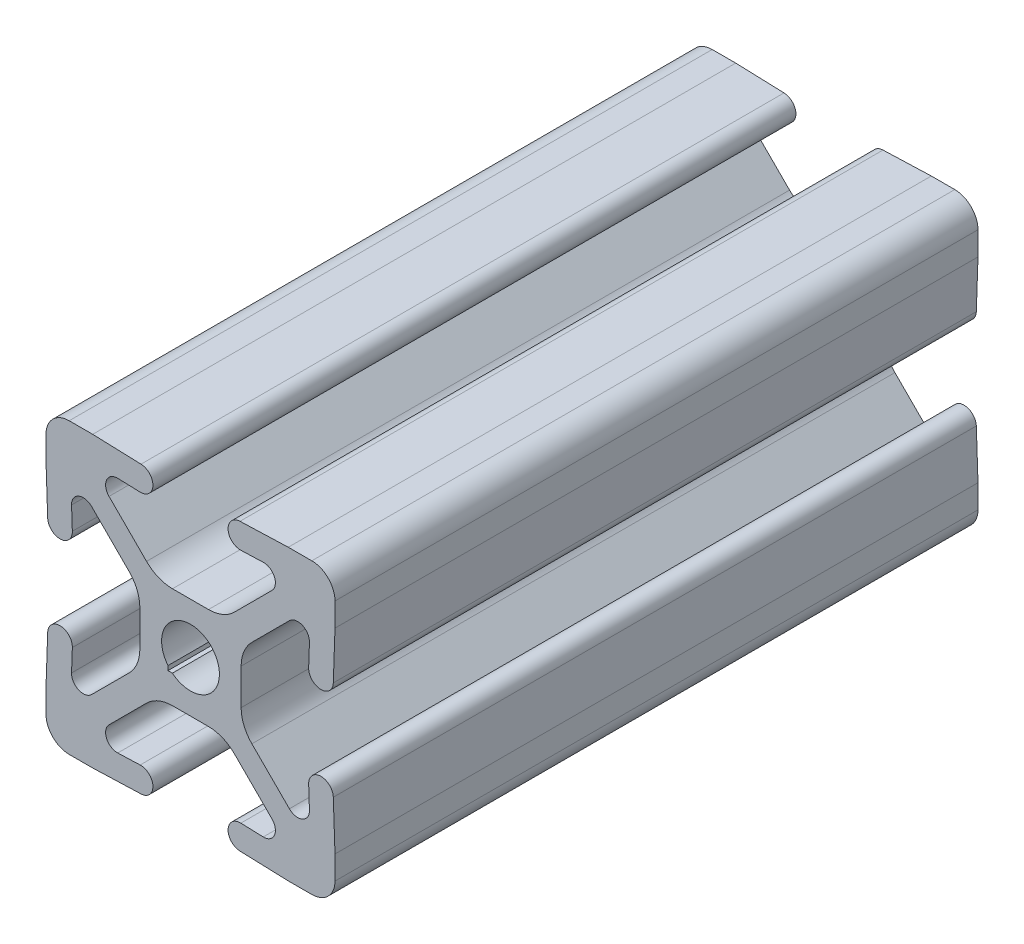
SolidWorks part; units mm, degrees
ref_plane "Front Plane" through (0, 0, 0) normal (0, 0, 1) x (1, 0, 0)
ref_plane "Top Plane" through (0, 0, 0) normal (0, 1, 0) x (1, 0, 0)
ref_plane "Right Plane" through (0, 0, 0) normal (1, 0, 0) x (0, 0, -1)
sketch "Model" plane through (0, 0, 0) normal (0, 0, 1) x (1, 0, 0)
  line L38 (50.6495, 75.4336) -> (50.2699, 75.4336)
  line L39 (50.2699, 75.4336) -> (50.2699, 75.8133)
  line L40 (50.66, 72.9999) -> (53.7746, 72.9999)
  line L41 (56.0196, 72.0699) -> (59.2642, 68.8254)
  line L42 (58.5103, 67.0916) -> (56.5725, 67.1592)
  line L43 (56.498, 65.0269) -> (60.6773, 64.881)
  line L44 (60.6773, 64.881) -> (62.7107, 64.881)
  line L45 (64.7173, 66.8876) -> (64.7173, 68.921)
  line L46 (64.7173, 68.921) -> (64.5713, 73.1002)
  line L47 (62.439, 73.0257) -> (62.5067, 71.0879)
  line L48 (60.7729, 70.334) -> (57.5283, 73.5786)
  line L49 (56.5984, 75.8237) -> (56.5984, 78.9383)
  line L50 (57.5283, 81.1833) -> (60.7729, 84.4279)
  line L51 (62.5067, 83.674) -> (62.439, 81.7362)
  line L52 (64.5713, 81.6617) -> (64.7173, 85.841)
  line L53 (64.7173, 85.841) -> (64.7173, 87.8744)
  line L54 (62.7107, 89.881) -> (60.6773, 89.881)
  line L55 (60.6773, 89.881) -> (56.498, 89.735)
  line L56 (56.5725, 87.6027) -> (58.5103, 87.6704)
  line L57 (59.2642, 85.9366) -> (56.0196, 82.692)
  line L58 (53.7746, 81.7621) -> (50.66, 81.7621)
  line L59 (48.4149, 82.692) -> (45.1703, 85.9366)
  line L60 (45.9242, 87.6704) -> (47.862, 87.6027)
  line L61 (47.9365, 89.735) -> (43.7573, 89.881)
  line L62 (43.7573, 89.881) -> (41.7239, 89.881)
  line L63 (39.7173, 87.8744) -> (39.7173, 85.841)
  line L64 (39.7173, 85.841) -> (39.8632, 81.6617)
  line L65 (41.9955, 81.7362) -> (41.9278, 83.674)
  line L66 (43.6616, 84.4279) -> (46.9062, 81.1833)
  line L67 (47.8361, 78.9383) -> (47.8361, 75.8237)
  line L68 (46.9062, 73.5786) -> (43.6616, 70.334)
  line L69 (41.9278, 71.0879) -> (41.9955, 73.0257)
  line L70 (39.8632, 73.1002) -> (39.7173, 68.921)
  line L71 (39.7173, 68.921) -> (39.7173, 66.8876)
  line L72 (41.7239, 64.881) -> (43.7573, 64.881)
  line L73 (43.7573, 64.881) -> (47.9365, 65.0269)
  line L74 (47.862, 67.1592) -> (45.9242, 67.0916)
  line L75 (45.1703, 68.8254) -> (48.4149, 72.0699)
  arc A29 (50.6495, 75.4336) -> (50.2699, 75.8133) centre (52.2173, 77.381) ccw
  arc A30 (56.0196, 72.0699) -> (53.7746, 72.9999) centre (53.7746, 69.8249) ccw
  arc A31 (58.5103, 67.0916) -> (59.2642, 68.8254) centre (58.5458, 68.1069) ccw
  arc A32 (56.5725, 67.1592) -> (56.498, 65.0269) centre (56.5353, 66.0931) ccw
  arc A33 (62.7107, 64.881) -> (64.7173, 66.8876) centre (62.7107, 66.8876) ccw
  arc A34 (64.5713, 73.1002) -> (62.439, 73.0257) centre (63.5052, 73.063) ccw
  arc A35 (60.7729, 70.334) -> (62.5067, 71.0879) centre (61.4913, 71.0525) ccw
  arc A36 (56.5984, 75.8237) -> (57.5283, 73.5786) centre (59.7734, 75.8237) ccw
  arc A37 (57.5283, 81.1833) -> (56.5984, 78.9383) centre (59.7734, 78.9383) ccw
  arc A38 (62.5067, 83.674) -> (60.7729, 84.4279) centre (61.4913, 83.7095) ccw
  arc A39 (62.439, 81.7362) -> (64.5713, 81.6617) centre (63.5052, 81.699) ccw
  arc A40 (64.7173, 87.8744) -> (62.7107, 89.881) centre (62.7107, 87.8744) ccw
  arc A41 (56.498, 89.735) -> (56.5725, 87.6027) centre (56.5353, 88.6689) ccw
  arc A42 (59.2642, 85.9366) -> (58.5103, 87.6704) centre (58.5458, 86.655) ccw
  arc A43 (53.7746, 81.7621) -> (56.0196, 82.692) centre (53.7746, 84.9371) ccw
  arc A44 (48.4149, 82.692) -> (50.66, 81.7621) centre (50.66, 84.9371) ccw
  arc A45 (45.9242, 87.6704) -> (45.1703, 85.9366) centre (45.8887, 86.655) ccw
  arc A46 (47.862, 87.6027) -> (47.9365, 89.735) centre (47.8993, 88.6689) ccw
  arc A47 (41.7239, 89.881) -> (39.7173, 87.8744) centre (41.7239, 87.8744) ccw
  arc A48 (39.8632, 81.6617) -> (41.9955, 81.7362) centre (40.9293, 81.699) ccw
  arc A49 (43.6616, 84.4279) -> (41.9278, 83.674) centre (42.9432, 83.7095) ccw
  arc A50 (47.8361, 78.9383) -> (46.9062, 81.1833) centre (44.6611, 78.9383) ccw
  arc A51 (46.9062, 73.5786) -> (47.8361, 75.8237) centre (44.6611, 75.8237) ccw
  arc A52 (41.9278, 71.0879) -> (43.6616, 70.334) centre (42.9432, 71.0525) ccw
  arc A53 (41.9955, 73.0257) -> (39.8632, 73.1002) centre (40.9293, 73.063) ccw
  arc A54 (39.7173, 66.8876) -> (41.7239, 64.881) centre (41.7239, 66.8876) ccw
  arc A55 (47.9365, 65.0269) -> (47.862, 67.1592) centre (47.8993, 66.0931) ccw
  arc A56 (45.1703, 68.8254) -> (45.9242, 67.0916) centre (45.8887, 68.1069) ccw
  arc A57 (50.66, 72.9999) -> (48.4149, 72.0699) centre (50.66, 69.8249) ccw
extrude "Boss-Extrude1" add sketch "Model" along normal blind 55.626
